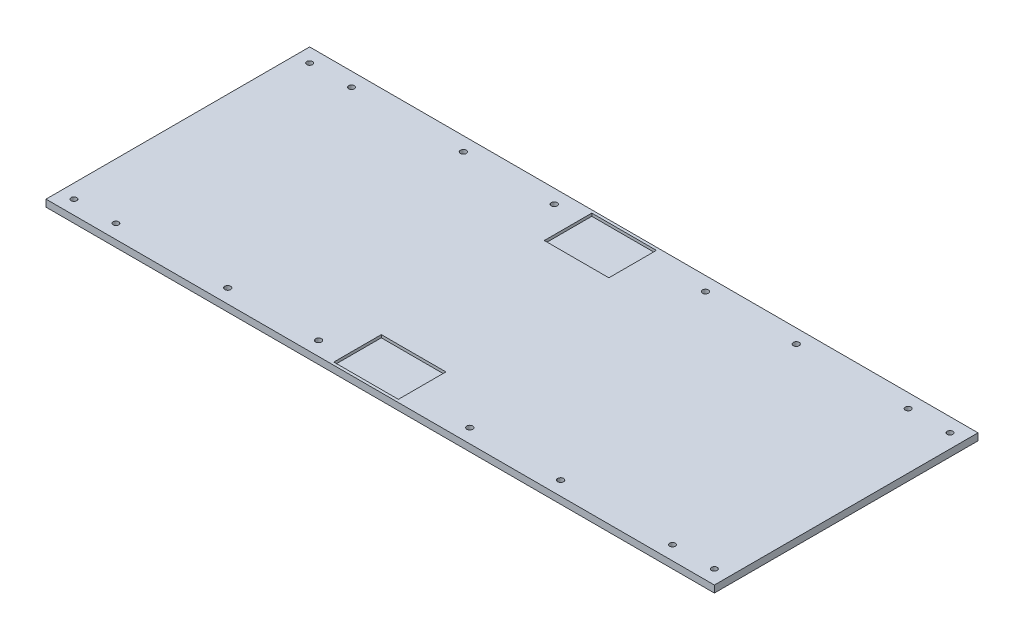
SolidWorks part; units mm, degrees
material "PMMA"
ref_plane "Plan de face" through (0, 0, 0) normal (0, 0, 1) x (1, 0, 0)
ref_plane "Plan de dessus" through (0, 0, 0) normal (0, 1, 0) x (1, 0, 0)
ref_plane "Plan de droite" through (0, 0, 0) normal (1, 0, 0) x (0, 0, -1)
sketch "Esquisse1" plane through (0, 0, 0) normal (0, 1, 0) x (1, 0, 0)
  line L1 (-72.9175, 141.3821) -> (405.2361, 141.3821)
  line L2 (-72.9175, 141.3821) -> (-72.9175, -47.2116)
  line L3 (-72.9175, -47.2116) -> (405.2361, -47.2116)
  line L4 (405.2361, 141.3821) -> (405.2361, -47.2116)
  line L5 (-72.9175, -47.2116) -> (-62.9175, -47.2116)
  line L6 (-72.9175, -47.2116) -> (-72.9175, -37.2116)
  line L9 (-72.9175, 141.3821) -> (-62.9175, 141.3821)
  line L10 (-72.9175, 141.3821) -> (-72.9175, 131.3821)
  line L13 (405.2361, 141.3821) -> (395.2361, 141.3821)
  line L14 (405.2361, 141.3821) -> (405.2361, 131.3821)
  line L17 (405.2361, -47.2116) -> (395.2361, -47.2116)
  line L18 (405.2361, -47.2116) -> (405.2361, -37.2116)
  circle A0 centre (-62.9175, 131.3821) radius 2
  circle A1 centre (-62.9175, -37.2116) radius 2
  circle A2 centre (395.2361, -37.2116) radius 2
  circle A3 centre (395.2361, 131.3821) radius 2
  circle A4 centre (-32.9175, -37.2116) radius 2
  circle A5 centre (-32.9175, 131.3821) radius 2
  circle A6 centre (365.2361, 131.3821) radius 2
  circle A7 centre (365.2361, -37.2116) radius 2
extrude "Boss.-Extru.4" add sketch "Esquisse1" along normal blind 5
sketch "Esquisse2" plane through (0, 5, 0) normal (0, 1, 0) x (1, 0, 0)
  line L0 (-72.9175, -47.2116) -> (166.1593, -47.2116)
  line L1 (-72.9175, -47.2116) -> (405.2361, -47.2116) construction
  line L2 (166.1593, -47.2116) -> (166.1593, 141.3821)
  line L3 (-72.9175, 141.3821) -> (405.2361, 141.3821) construction
  line L4 (166.1593, -47.2116) -> (177.1593, -47.2116)
  line L5 (177.1593, -47.2116) -> (177.1593, 141.3821)
  line L6 (166.1593, 141.3821) -> (166.1593, 139.3821)
  line L7 (166.1593, 139.3821) -> (177.1593, 139.3821)
  line L8 (177.1593, -47.2116) -> (177.1593, -45.2116)
  line L9 (177.1593, -45.2116) -> (166.1593, -45.2116)
  line L10 (177.1593, -45.2116) -> (130.9593, -45.2116)
  line L11 (130.9593, -45.2116) -> (130.9593, 141.3821)
  line L12 (166.1593, 139.3821) -> (130.9593, 139.3821)
  line L13 (130.9593, -45.2116) -> (130.9593, -11.2116)
  line L14 (130.9593, -11.2116) -> (177.1593, -11.2116)
  line L15 (177.1593, 139.3821) -> (177.1593, 105.3821)
  line L16 (177.1593, 105.3821) -> (130.9593, 105.3821)
extrude "Enlèv. mat.-Extru.1" cut sketch "Esquisse2" against normal blind 2 contours L16 L2 L12 L11 | L16 L5 L7 L2 | L14 L11 L10 L2 | L14 L2 L9 L5
sketch "Esquisse3" plane through (0, 5, 0) normal (0, 1, 0) x (1, 0, 0)
  line L0 (-32.9175, 131.3821) -> (47.0825, 131.3821)
  line L1 (-32.9175, -37.2116) -> (47.0825, -37.2116)
  line L2 (365.2361, 131.3821) -> (285.2361, 131.3821)
  line L3 (365.2361, -37.2116) -> (285.2361, -37.2116)
  line L4 (47.0825, 131.3821) -> (112.0825, 131.3821)
  line L5 (47.0825, -37.2116) -> (112.0825, -37.2116)
  line L6 (285.2361, 131.3821) -> (220.2361, 131.3821)
  line L7 (285.2361, -37.2116) -> (220.2361, -37.2116)
  circle A0 centre (47.0825, 131.3821) radius 2.1
  circle A1 centre (47.0825, -37.2116) radius 2.1
  circle A2 centre (285.2361, 131.3821) radius 2.1
  circle A3 centre (285.2361, -37.2116) radius 2.1
  circle A4 centre (220.2361, 131.3821) radius 2.1
  circle A5 centre (220.2361, -37.2116) radius 2.1
  circle A6 centre (112.0825, 131.3821) radius 2.1
  circle A7 centre (112.0825, -37.2116) radius 2.1
  dimension "D5" = 65
  dimension "D1" = 80
  dimension "D2" = 80
  dimension "D3" = 80
  dimension "D4" = 80
  dimension "D6" = 65
  dimension "D7" = 65
  dimension "D8" = 65
extrude "Enlèv. mat.-Extru.2" cut sketch "Esquisse3" against normal blind 10 contours A2 | A4 | A3 | A5 | A7 | A1 | A0 | A6
